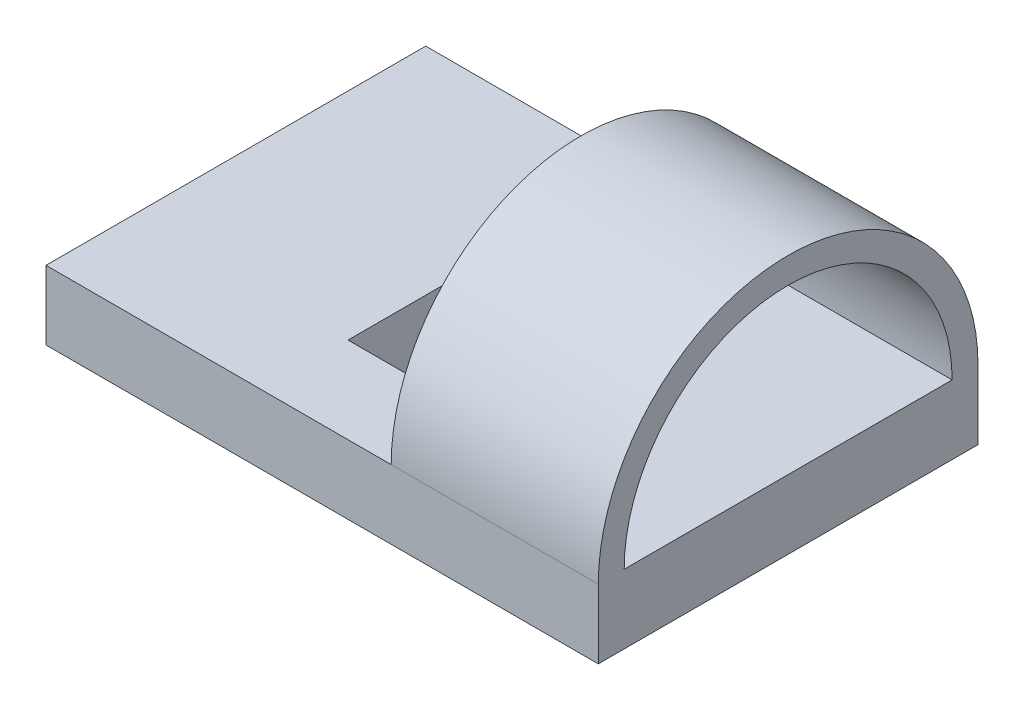
SolidWorks part; units mm, degrees
ref_plane "前视基准面" through (0, 0, 0) normal (0, 0, 1) x (1, 0, 0)
ref_plane "上视基准面" through (0, 0, 0) normal (0, 1, 0) x (1, 0, 0)
ref_plane "右视基准面" through (0, 0, 0) normal (1, 0, 0) x (0, 0, -1)
sketch "草图1" plane through (0, 0, 0) normal (0, 1, 0) x (1, 0, 0)
  line L1 (-8, -5.5) -> (8, -5.5)
  line L2 (-8, -5.5) -> (-8, 5.5)
  line L3 (-8, 5.5) -> (8, 5.5)
  line L4 (8, -5.5) -> (8, 5.5)
  point P0 (0, 0)
  point P6 (8, 0)
  dimension "D1" = 16
  dimension "D2" = 11
  dimension "D3" = 8
extrude "凸台-拉伸1" add sketch "草图1" along normal blind 2
sketch "草图2" plane through (0, 0, 0) normal (1, 0, 0) x (0, 0, -1)
  line L0 (-5.5, 2) -> (5.5, 2) construction
  line L1 (-5.5, 2) -> (-4.75, 2)
  line L2 (4.75, 2) -> (5.5, 2)
  arc A0 (5.5, 2) -> (-5.5, 2) centre (0, 2) ccw
  arc A1 (4.75, 2) -> (-4.75, 2) centre (0, 2) ccw
  dimension "D1" = 11
  dimension "D2" = 9.5
extrude "凸台-拉伸2" add sketch "草图2" along normal blind 6 from offset 2
sketch "草图3" plane through (0, 0, 0) normal (0, -1, 0) x (1, 0, 0)
  line L0 (-1.75, 3) -> (-1.75, -3)
  line L1 (1.75, 3) -> (1.75, -3)
  line L2 (1.75, -3) -> (-1.75, -3)
  line L3 (1.75, 3) -> (-1.75, 3)
  point P0 (1.75, 0)
  point P1 (-1.75, 0)
  point P4 (0, 3)
  dimension "D1" = 6
  dimension "D2" = 3.5
extrude "切除-拉伸1" cut sketch "草图3" against normal through all
mirror "镜向1" [suppressed] about plane through (0, 0, 0) normal (1, 0, 0)
